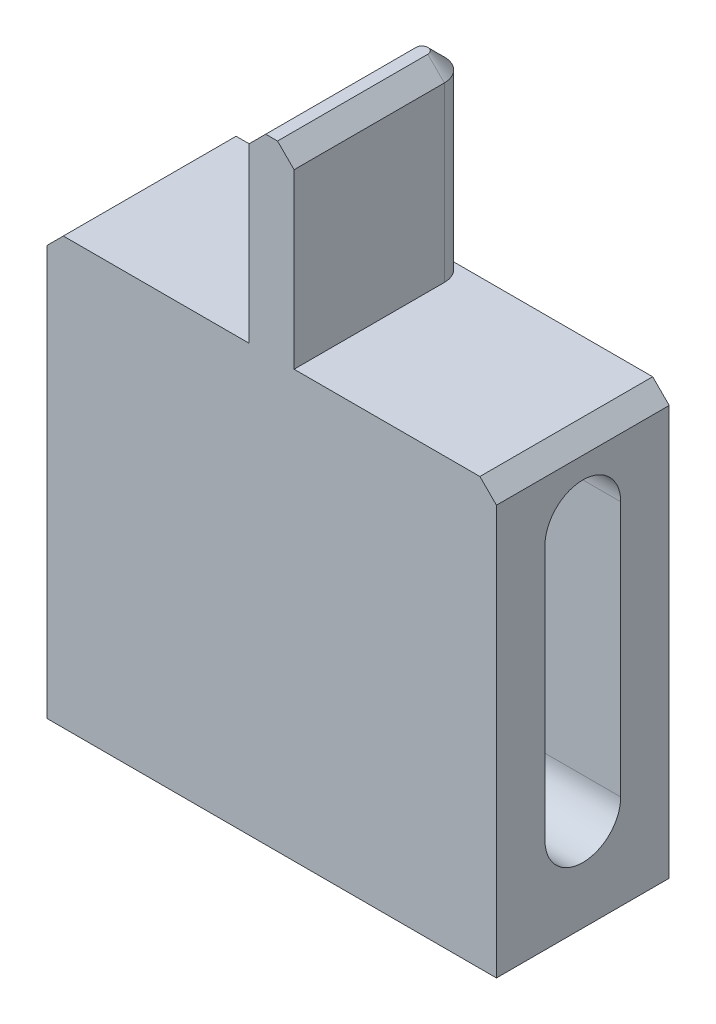
SolidWorks part; units mm, degrees
ref_plane "Front Plane" through (0, 0, 0) normal (0, 0, 1) x (1, 0, 0)
ref_plane "Top Plane" through (0, 0, 0) normal (0, 1, 0) x (1, 0, 0)
ref_plane "Right Plane" through (0, 0, 0) normal (1, 0, 0) x (0, 0, -1)
sketch "Sketch1" plane through (0, 0, 0) normal (0, 0, 1) x (1, 0, 0)
  line L0 (9.5, 0) -> (9.5, 26) construction
  line L1 (0, 0) -> (19, 0)
  line L2 (0, 0) -> (0, 18)
  line L3 (0, 18) -> (8.55, 18)
  line L4 (19, 0) -> (19, 18)
  line L6 (8.55, 18) -> (8.55, 26)
  line L7 (8.55, 26) -> (10.45, 26)
  line L8 (10.45, 18) -> (10.45, 26)
  line L11 (10.45, 18) -> (19, 18)
  point P11 (9.5, 26)
  point P13 (0, 0)
  dimension "D1" = 0
  dimension "D2" = 1.9
  dimension "D3" = 19
  dimension "D4" = 8
  dimension "D5" = 18
extrude "Boss-Extrude1" add sketch "Sketch1" along normal blind 7.3
sketch "Sketch2" plane through (0, 26, 0) normal (0, 1, 0) x (1, 0, 0)
  line L0 (9.5, 0) -> (9.5, -4.71) construction
  line L1 (10.45, 0) -> (8.55, 0) construction
  line L2 (8.55, -0.95) -> (8.55, 0)
  line L3 (8.55, 0) -> (9.5, 0)
  arc A0 (9.5, 0) -> (8.55, -0.95) centre (9.5, -0.95) ccw
  dimension "D2" = 0.95
extrude "Cut-Extrude1" cut sketch "Sketch2" against normal up to surface (8 mm away) up to face at (4.275, 18, 3.65)
sketch "Sketch3" plane through (0, 26, 0) normal (0, 1, 0) x (1, 0, 0)
  line L0 (9.5, 0) -> (10.45, 0)
  line L1 (10.45, 0) -> (10.45, -0.95)
  arc A0 (10.45, -0.95) -> (9.5, 0) centre (9.5, -0.95) ccw
  dimension "D1" = 1.9
extrude "Cut-Extrude2" cut sketch "Sketch3" against normal up to surface (8 mm away) up to face at (14.725, 18, 3.65)
sketch "Sketch4" plane through (19, 0, 0) normal (1, 0, 0) x (0, 0, -1)
  line L0 (-3.65, 18) -> (-3.65, 0) construction
  line L1 (-7.3, 18) -> (0, 18) construction
  line L2 (-7.3, 0) -> (0, 0) construction
  line L3 (-5.25, 14.8) -> (-5.25, 4)
  line L4 (-2.05, 14.8) -> (-2.05, 4)
  arc A0 (-2.05, 14.8) -> (-5.25, 14.8) centre (-3.65, 14.8) ccw
  arc A1 (-5.25, 4) -> (-2.05, 4) centre (-3.65, 4) ccw
  dimension "D1" = 3.2
  dimension "D2" = 3.2
  dimension "D3" = 4
extrude "Cut-Extrude3" cut sketch "Sketch4" against normal through all both and the other way through all
chamfer "Chamfer1" distance 0.7 angle 45 5 edges at (0, 18, 3.65) (19, 18, 3.65) (10.45, 26, 4.125) (9.5, 26, 0) (8.55, 26, 4.125)
